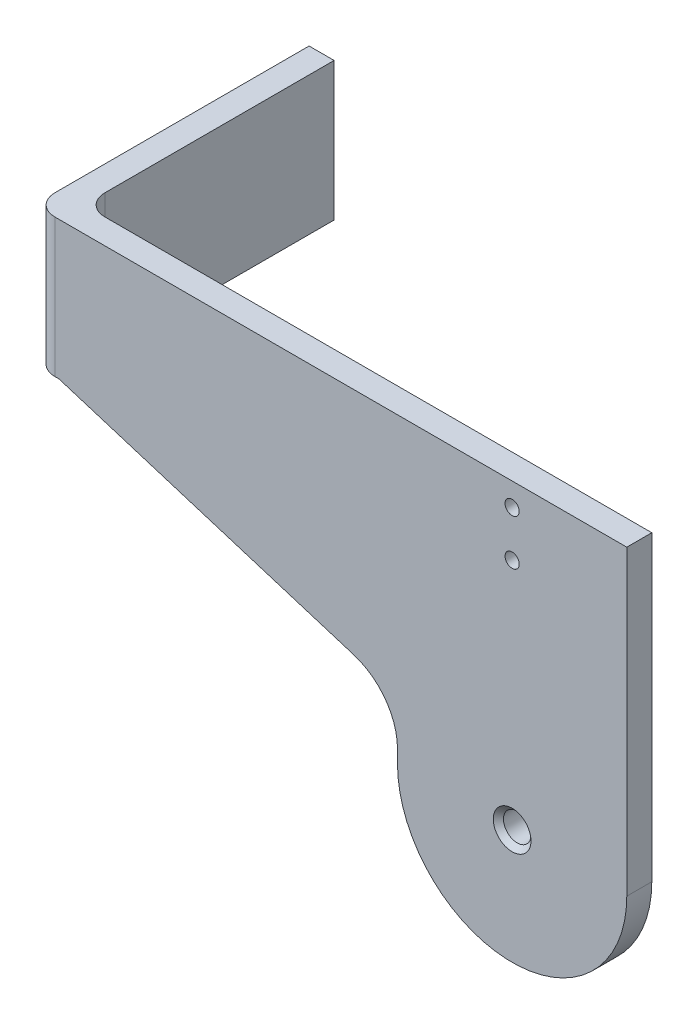
SolidWorks part; units mm, degrees
ref_plane "Piano frontale" through (0, 0, 0) normal (0, 0, 1) x (1, 0, 0)
ref_plane "Piano superiore" through (0, 0, 0) normal (0, 1, 0) x (1, 0, 0)
ref_plane "Piano destro" through (0, 0, 0) normal (1, 0, 0) x (0, 0, -1)
sketch "Schizzo2" plane through (0, 0, 0) normal (0, 0, 1) x (1, 0, 0)
  line L0 (0, 0) -> (0, 45) construction
  line L1 (-27.5, 0) -> (-27.5, 45)
  line L2 (27.5, 0) -> (27.5, 45)
  arc A0 (-27.5, 0) -> (27.5, 0) centre (0, 0) ccw
  arc A1 (27.5, 45) -> (-27.5, 45) centre (0, 45) ccw
  point P3 (0, 22.5)
  point P8 (0, -27.5)
  point P9 (0, 72.5)
  dimension "D1" = 100
  dimension "D2" = 55
extrude "Estrusione-Estrusione1" add sketch "Schizzo2" along normal blind 6
sketch "Schizzo3" plane through (0, 0, 0) normal (0, 0, 1) x (1, 0, 0)
  line L1 (27.5, 0) -> (-108.7, 0)
  line L2 (27.5, 0) -> (27.5, 72.5)
  line L3 (27.5, 72.5) -> (-108.7, 72.5)
  line L4 (-108.7, 0) -> (-108.7, 72.5)
  arc A0 (27.5, 45) -> (-27.5, 45) centre (0, 45) ccw construction
  point P9 (0, 72.5)
  dimension "D1" = 136.2
  dimension "D2" = 72.5
  dimension "D3" = 72.5
extrude "Estrusione-Estrusione2" add sketch "Schizzo3" along normal blind 6
sketch "Schizzo4" plane through (0, 0, 6) normal (0, 0, 1) x (1, 0, 0)
  line L2 (-27.5, 0) -> (-108.7, 0)
  line L3 (-108.7, 0) -> (-108.7, 39.3472)
  line L4 (-108.7, 39.3472) -> (-27.5, 14.1424)
  line L5 (-27.5, 14.1424) -> (-27.5, 0)
  line L6 (-108.7, 72.5) -> (-108.7, 0) construction
extrude "Taglio-Estrusione1" cut sketch "Schizzo4" against normal through all
fillet "Raccordo5" radius 15 1 edges at (-27.5, 14.1424, 3)
sketch "Schizzo9" plane through (0, 0, 0) normal (0, 0, 1) x (1, 0, 0)
  line L0 (-108.7, 39.3472) -> (-114.7, 39.3472)
  line L1 (-114.7, 39.3472) -> (-114.7, 72.5)
  line L2 (-114.7, 72.5) -> (-108.7, 72.5)
  line L3 (-108.7, 72.5) -> (-108.7, 39.3472)
extrude "Estrusione-Estrusione5" add sketch "Schizzo9" against normal blind 60 and the other way up to vertex (6 mm away) other way up to point (-108.7, 72.5, 6)
fillet "Raccordo6" radius 5 1 edges at (-108.7, 55.9236, 0)
fillet "Raccordo7" radius 5 1 edges at (-114.7, 55.9236, 6)
sketch "Schizzo10" plane through (0, 0, 0) normal (0, 0, -1) x (-1, 0, 0)
  line L0 (0, 72.5) -> (0, 67) construction
  line L1 (-27.5, 72.5) -> (103.7, 72.5) construction
  line L2 (0, 67) -> (0, 56.05) construction
  dimension "D1" = 5.5
  dimension "D2" = 10.95
hole_wizard "Foro filettato G1/16-1" positions "Schizzo15" profile "Schizzo16" tap size "G1/16" standard "GB" end condition through all
sketch "Schizzo15" plane through (0, 0, 6) normal (0, 0, 1) x (1, 0, 0)
  point P0 (0, 0)
sketch "Schizzo16" plane through (0, 0, 6) normal (1, 0, 0) x (0, -1, 0)
  line L0 (0, 0) -> (0, 66)
  line L1 (0, 66) -> (3.3, 66)
  line L2 (3.3, 66) -> (3.3, 1.225)
  line L3 (3.3, 1.225) -> (4.525, 0)
  line L5 (4.525, 0) -> (0, 0)
  line L6 (-3.3, 1.225) -> (-4.525, 0) construction
  line L11 (0, -6.35) -> (0, 107.95) construction
  dimension "Thru Tap Drill Dia." = 6.6
  dimension "Thru Tap Drill Depth" = 66
  dimension "Near C'Sink Dia." = 9.05
  dimension "Near C'Sink Angle" = 90
cosmetic thread "Filettatura del foro1" parameters "D2"=7.723
hole_wizard "Foro lamato per Bullone M3 a testa esagonale-3" positions "Schizzo19" profile "Schizzo20" size "M3" standard "GB" slot yes end condition through all
sketch "Schizzo19" plane through (0, 0, 0) normal (0, 0, -1) x (-1, 0, 0)
  point P0 (0, 67)
  point P3 (0, 56.05)
sketch "Schizzo20" plane through (0, 67, 0) normal (1, 0, 0) x (0, 1, 0)
  line L0 (0, 0) -> (0, 6)
  line L1 (0, 6) -> (1.7, 6)
  line L3 (1.7, 6) -> (1.7, 0.5)
  line L4 (4.5, 0.5) -> (1.7, 0.5)
  line L5 (4.5, 0.5) -> (4.5, 0.025)
  line L6 (4.5, 0.025) -> (4.525, 0)
  line L7 (4.525, 0) -> (0, 0)
  line L8 (-4.5, 0.025) -> (-4.525, 0) construction
  line L11 (0, -6.35) -> (0, 107.95) construction
  dimension "Thru Hole Dia." = 3.4
  dimension "Thru Hole Depth" = 6
  dimension "C'Bore Dia." = 9
  dimension "C'Bore Depth" = 0.5
  dimension "Near C'Sink Dia." = 9.05
  dimension "Near C'Sink Angle" = 90
